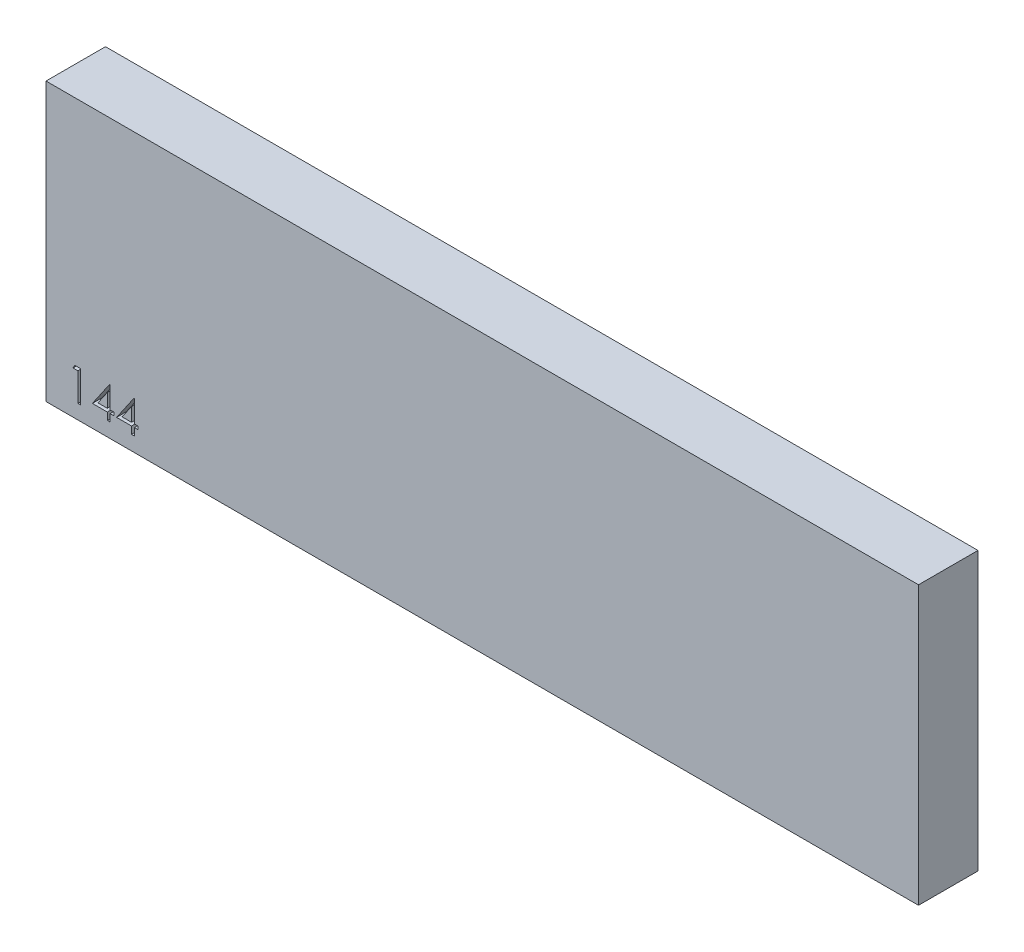
SolidWorks part; units mm, degrees
material "Acrylic (Medium-high impact)"
ref_plane "Front Plane" through (0, 0, 0) normal (0, 0, 1) x (1, 0, 0)
ref_plane "Top Plane" through (0, 0, 0) normal (0, 1, 0) x (1, 0, 0)
ref_plane "Right Plane" through (0, 0, 0) normal (1, 0, 0) x (0, 0, -1)
sketch "Sketch1" plane through (0, 0, 0) normal (0, 0, 1) x (1, 0, 0)
  line L1 (-44, 14) -> (44, 14)
  line L2 (-44, 14) -> (-44, -14)
  line L3 (-44, -14) -> (44, -14)
  line L4 (44, 14) -> (44, -14)
  line L5 (-44, 14) -> (44, -14) construction
  line L6 (-44, -14) -> (44, 14) construction
  point P0 (0, 0)
  dimension "D1" = 88
  dimension "D2" = 28
extrude "Boss-Extrude1" add sketch "Sketch1" along normal blind 6
sketch "Sketch2" plane through (0, 0, 6) normal (0, 0, 1) x (1, 0, 0)
  text T0 "144"
extrude "Cut-Extrude1" cut sketch "Sketch2" against normal blind 1
